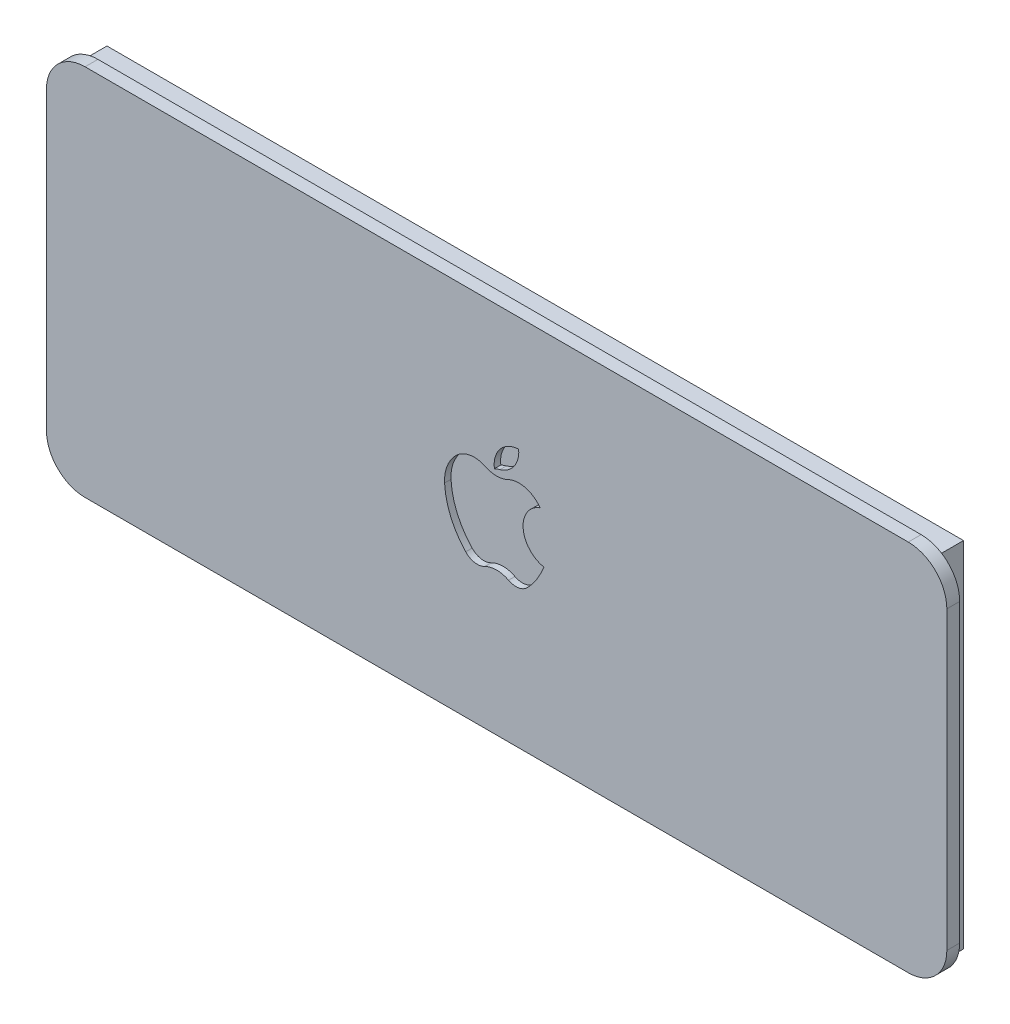
SolidWorks part; units mm, degrees
ref_plane "前视基准面" through (0, 0, 0) normal (0, 0, 1) x (1, 0, 0)
ref_plane "上视基准面" through (0, 0, 0) normal (0, 1, 0) x (1, 0, 0)
ref_plane "右视基准面" through (0, 0, 0) normal (1, 0, 0) x (0, 0, -1)
sketch "草图1" plane through (0, 0, 0) normal (0, 0, 1) x (1, 0, 0)
  line L1 (-64, 29) -> (64, 29)
  line L2 (-70, 23) -> (-70, -23)
  line L3 (-64, -29) -> (64, -29)
  line L4 (70, 23) -> (70, -23)
  line L5 (-70, 29) -> (70, -29) construction
  line L6 (-70, -29) -> (70, 29) construction
  arc A0 (-64, -29) -> (-70, -23) centre (-64, -23) cw
  arc A1 (64, -29) -> (70, -23) centre (64, -23) ccw
  arc A2 (64, 29) -> (70, 23) centre (64, 23) cw
  arc A3 (-70, 23) -> (-64, 29) centre (-64, 23) cw
  point P0 (0, 0)
  dimension "D3" = 6
  dimension "D4" = 6
  dimension "D1" = 140
  dimension "D2" = 58
extrude "凸台-拉伸1" add sketch "草图1" along normal blind 2
sketch "草图3" plane through (0, 0, 2) normal (0, 0, 1) x (1, 0, 0)
  arc A1 (1.8462, -7.2178) -> (4.8117, -6.7227) centre (3, -5) ccw
  arc A2 (-1.8462, -7.2178) -> (-4.8117, -6.7227) centre (-3, -5) cw
  arc A3 (-1.7375, 6.2866) -> (-6.2113, 5.6014) centre (-3.475, 2.6837) ccw
  arc A9 (-8.0982, 0.9036) -> (-4.8117, -6.7227) centre (3.8845, 1.5462) ccw
  arc A14 (1.8462, -7.2178) -> (-1.8462, -7.2178) centre (0, -10.7663) ccw
  arc A16 (6.7735, 4.9961) -> (7.3388, -2.7007) centre (8.1068, 1.2249) ccw
  arc A17 (0.5065, 7.0075) -> (3.4236, 11.2205) centre (-0.5604, 10.8626) ccw
  arc A18 (7.3388, -2.7007) -> (4.8117, -6.7227) centre (-3.8845, 1.5462) cw
  arc A25 (6.2113, 5.6014) -> (6.7735, 4.9961) centre (2.1068, 1.2249) cw
  arc A28 (-1.7375, 6.2866) -> (1.7375, 6.2866) centre (0, 9.8896) ccw
  arc A30 (-6.2113, 5.6014) -> (-8.0982, 0.9036) centre (-2.1068, 1.2249) ccw
  arc A32 (-0.3544, 6.6969) -> (0.5065, 7.0075) centre (2.1068, 1.2249) cw
  arc A35 (1.7375, 6.2866) -> (6.2113, 5.6014) centre (3.475, 2.6837) cw
  arc A38 (3.4236, 11.2205) -> (-0.3544, 6.6969) centre (3.6106, 7.2249) ccw
  dimension "D2" = 5
extrude "切除-拉伸2" cut sketch "草图3" against normal blind 1
sketch "草图4" plane through (0, 0, 0) normal (0, 0, -1) x (-1, 0, 0)
  line L1 (-66.595, 27.5) -> (66.595, 27.5)
  line L2 (-66.595, 27.5) -> (-66.595, -27.5)
  line L3 (-66.595, -27.5) -> (66.595, -27.5)
  line L4 (66.595, 27.5) -> (66.595, -27.5)
  line L5 (-66.595, 27.5) -> (66.595, -27.5) construction
  line L6 (-66.595, -27.5) -> (66.595, 27.5) construction
  line L7 (-65.095, 26.8806) -> (65.095, 26.8806)
  line L8 (-65.095, 26.8806) -> (-65.095, -26.8806)
  line L9 (-65.095, -26.8806) -> (65.095, -26.8806)
  line L10 (65.095, 26.8806) -> (65.095, -26.8806)
  line L11 (-65.095, 26.8806) -> (65.095, -26.8806) construction
  line L12 (-65.095, -26.8806) -> (65.095, 26.8806) construction
  point P0 (0, 0)
  point P6 (0, 0)
  dimension "D1" = 133.19
  dimension "D2" = 55
  dimension "D3" = 1.5
extrude "凸台-拉伸2" add sketch "草图4" along normal blind 4
